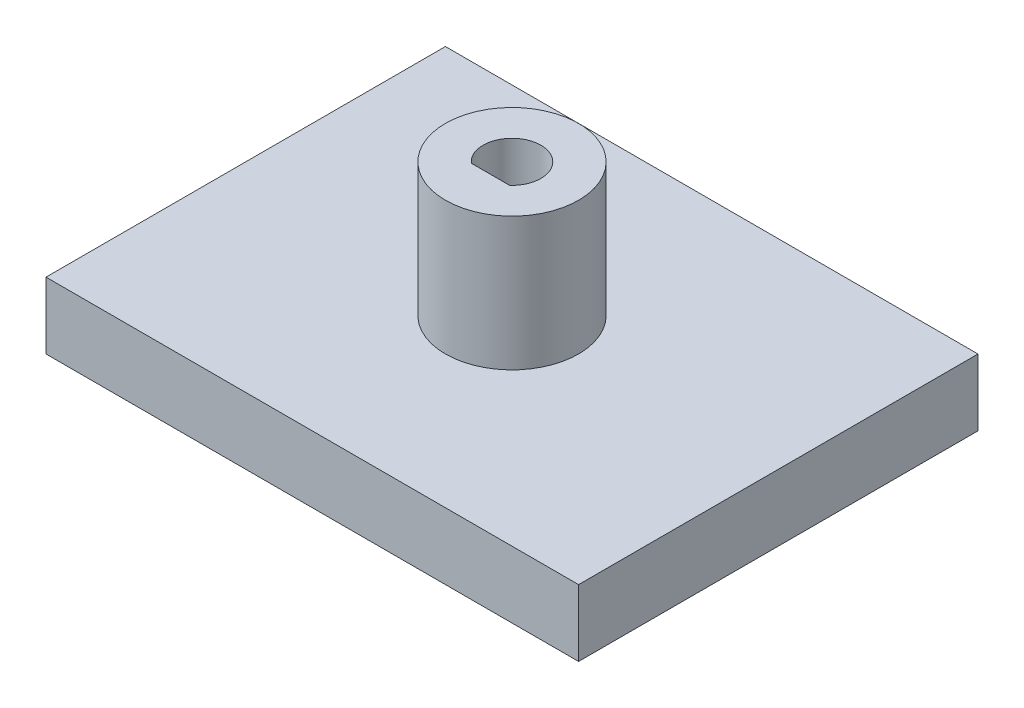
SolidWorks part; units mm, degrees
ref_plane "Front Plane" through (0, 0, 0) normal (0, 0, 1) x (1, 0, 0)
ref_plane "Top Plane" through (0, 0, 0) normal (0, 1, 0) x (1, 0, 0)
ref_plane "Right Plane" through (0, 0, 0) normal (1, 0, 0) x (0, 0, -1)
sketch "Sketch1" plane through (0, 0, 0) normal (0, 1, 0) x (1, 0, 0)
  line L1 (0, 0) -> (50.8, 0)
  line L2 (0, 0) -> (0, 38.1)
  line L3 (0, 38.1) -> (50.8, 38.1)
  line L4 (50.8, 0) -> (50.8, 38.1)
  dimension "D1" = 50.8
  dimension "D2" = 38.1
extrude "Boss-Extrude1" add sketch "Sketch1" along normal blind 6.35
sketch "Sketch2" plane through (0, 6.35, 0) normal (0, 1, 0) x (1, 0, 0)
  line L0 (0, 0) -> (50.8, 0) construction
  line L1 (50.8, 0) -> (50.8, 38.1) construction
  line L2 (23.5702, 16.9926) -> (27.2298, 16.9926)
  circle A0 centre (25.4, 19.05) radius 6.35
  arc A1 (27.2298, 16.9926) -> (23.5702, 16.9926) centre (25.4, 19.05) ccw
  point P4 (25.4, 0)
  dimension "D3" = 12.7
  dimension "D4" = 5.5067
  dimension "D1" = 19.05
  dimension "D2" = 25.4
  dimension "D5" = 2.0574
extrude "Boss-Extrude2" add sketch "Sketch2" along normal blind 12.7
